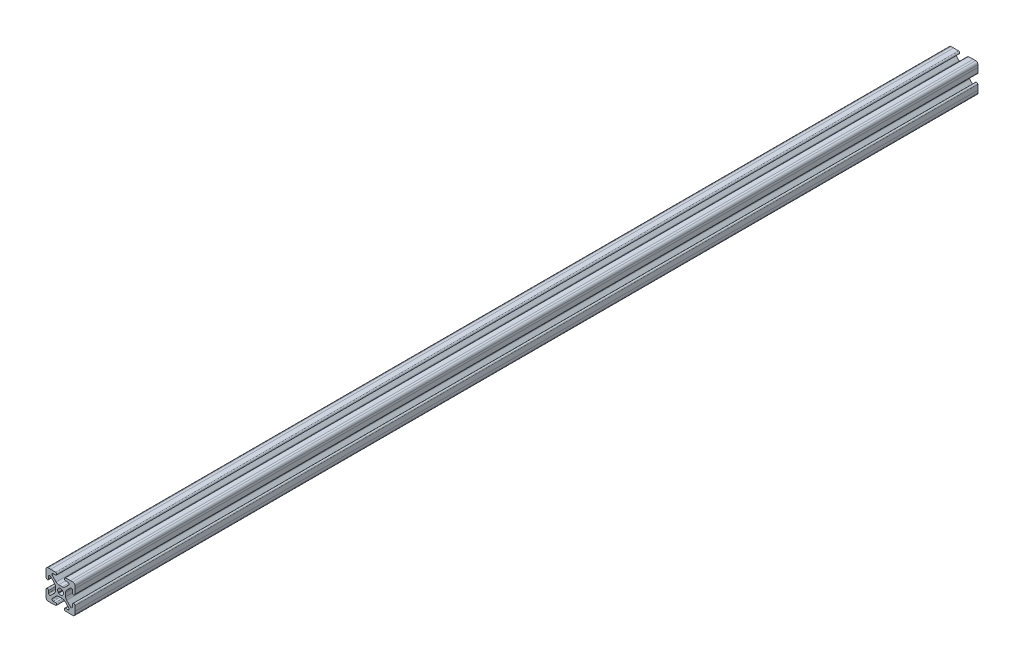
SolidWorks part; units mm, degrees
ref_plane "Front Plane" through (0, 0, 0) normal (0, 0, 1) x (1, 0, 0)
ref_plane "Top Plane" through (0, 0, 0) normal (0, 1, 0) x (1, 0, 0)
ref_plane "Right Plane" through (0, 0, 0) normal (1, 0, 0) x (0, 0, -1)
sketch "Model" plane through (0, 0, 0) normal (0, 0, 1) x (1, 0, 0)
  line L38 (50.6495, 75.4336) -> (50.2699, 75.4336)
  line L39 (50.2699, 75.4336) -> (50.2699, 75.8133)
  line L40 (50.66, 72.9999) -> (53.7746, 72.9999)
  line L41 (56.0196, 72.0699) -> (59.2642, 68.8254)
  line L42 (58.5103, 67.0916) -> (56.5725, 67.1592)
  line L43 (56.498, 65.0269) -> (60.6773, 64.881)
  line L44 (60.6773, 64.881) -> (62.7107, 64.881)
  line L45 (64.7173, 66.8876) -> (64.7173, 68.921)
  line L46 (64.7173, 68.921) -> (64.5713, 73.1002)
  line L47 (62.439, 73.0257) -> (62.5067, 71.0879)
  line L48 (60.7729, 70.334) -> (57.5283, 73.5786)
  line L49 (56.5984, 75.8237) -> (56.5984, 78.9383)
  line L50 (57.5283, 81.1833) -> (60.7729, 84.4279)
  line L51 (62.5067, 83.674) -> (62.439, 81.7362)
  line L52 (64.5713, 81.6617) -> (64.7173, 85.841)
  line L53 (64.7173, 85.841) -> (64.7173, 87.8744)
  line L54 (62.7107, 89.881) -> (60.6773, 89.881)
  line L55 (60.6773, 89.881) -> (56.498, 89.735)
  line L56 (56.5725, 87.6027) -> (58.5103, 87.6704)
  line L57 (59.2642, 85.9366) -> (56.0196, 82.692)
  line L58 (53.7746, 81.7621) -> (50.66, 81.7621)
  line L59 (48.4149, 82.692) -> (45.1703, 85.9366)
  line L60 (45.9242, 87.6704) -> (47.862, 87.6027)
  line L61 (47.9365, 89.735) -> (43.7573, 89.881)
  line L62 (43.7573, 89.881) -> (41.7239, 89.881)
  line L63 (39.7173, 87.8744) -> (39.7173, 85.841)
  line L64 (39.7173, 85.841) -> (39.8632, 81.6617)
  line L65 (41.9955, 81.7362) -> (41.9278, 83.674)
  line L66 (43.6616, 84.4279) -> (46.9062, 81.1833)
  line L67 (47.8361, 78.9383) -> (47.8361, 75.8237)
  line L68 (46.9062, 73.5786) -> (43.6616, 70.334)
  line L69 (41.9278, 71.0879) -> (41.9955, 73.0257)
  line L70 (39.8632, 73.1002) -> (39.7173, 68.921)
  line L71 (39.7173, 68.921) -> (39.7173, 66.8876)
  line L72 (41.7239, 64.881) -> (43.7573, 64.881)
  line L73 (43.7573, 64.881) -> (47.9365, 65.0269)
  line L74 (47.862, 67.1592) -> (45.9242, 67.0916)
  line L75 (45.1703, 68.8254) -> (48.4149, 72.0699)
  arc A29 (50.6495, 75.4336) -> (50.2699, 75.8133) centre (52.2173, 77.381) ccw
  arc A30 (56.0196, 72.0699) -> (53.7746, 72.9999) centre (53.7746, 69.8249) ccw
  arc A31 (58.5103, 67.0916) -> (59.2642, 68.8254) centre (58.5458, 68.1069) ccw
  arc A32 (56.5725, 67.1592) -> (56.498, 65.0269) centre (56.5353, 66.0931) ccw
  arc A33 (62.7107, 64.881) -> (64.7173, 66.8876) centre (62.7107, 66.8876) ccw
  arc A34 (64.5713, 73.1002) -> (62.439, 73.0257) centre (63.5052, 73.063) ccw
  arc A35 (60.7729, 70.334) -> (62.5067, 71.0879) centre (61.4913, 71.0525) ccw
  arc A36 (56.5984, 75.8237) -> (57.5283, 73.5786) centre (59.7734, 75.8237) ccw
  arc A37 (57.5283, 81.1833) -> (56.5984, 78.9383) centre (59.7734, 78.9383) ccw
  arc A38 (62.5067, 83.674) -> (60.7729, 84.4279) centre (61.4913, 83.7095) ccw
  arc A39 (62.439, 81.7362) -> (64.5713, 81.6617) centre (63.5052, 81.699) ccw
  arc A40 (64.7173, 87.8744) -> (62.7107, 89.881) centre (62.7107, 87.8744) ccw
  arc A41 (56.498, 89.735) -> (56.5725, 87.6027) centre (56.5353, 88.6689) ccw
  arc A42 (59.2642, 85.9366) -> (58.5103, 87.6704) centre (58.5458, 86.655) ccw
  arc A43 (53.7746, 81.7621) -> (56.0196, 82.692) centre (53.7746, 84.9371) ccw
  arc A44 (48.4149, 82.692) -> (50.66, 81.7621) centre (50.66, 84.9371) ccw
  arc A45 (45.9242, 87.6704) -> (45.1703, 85.9366) centre (45.8887, 86.655) ccw
  arc A46 (47.862, 87.6027) -> (47.9365, 89.735) centre (47.8993, 88.6689) ccw
  arc A47 (41.7239, 89.881) -> (39.7173, 87.8744) centre (41.7239, 87.8744) ccw
  arc A48 (39.8632, 81.6617) -> (41.9955, 81.7362) centre (40.9293, 81.699) ccw
  arc A49 (43.6616, 84.4279) -> (41.9278, 83.674) centre (42.9432, 83.7095) ccw
  arc A50 (47.8361, 78.9383) -> (46.9062, 81.1833) centre (44.6611, 78.9383) ccw
  arc A51 (46.9062, 73.5786) -> (47.8361, 75.8237) centre (44.6611, 75.8237) ccw
  arc A52 (41.9278, 71.0879) -> (43.6616, 70.334) centre (42.9432, 71.0525) ccw
  arc A53 (41.9955, 73.0257) -> (39.8632, 73.1002) centre (40.9293, 73.063) ccw
  arc A54 (39.7173, 66.8876) -> (41.7239, 64.881) centre (41.7239, 66.8876) ccw
  arc A55 (47.9365, 65.0269) -> (47.862, 67.1592) centre (47.8993, 66.0931) ccw
  arc A56 (45.1703, 68.8254) -> (45.9242, 67.0916) centre (45.8887, 68.1069) ccw
  arc A57 (50.66, 72.9999) -> (48.4149, 72.0699) centre (50.66, 69.8249) ccw
extrude "Boss-Extrude1" add sketch "Model" along normal blind 777.3416
